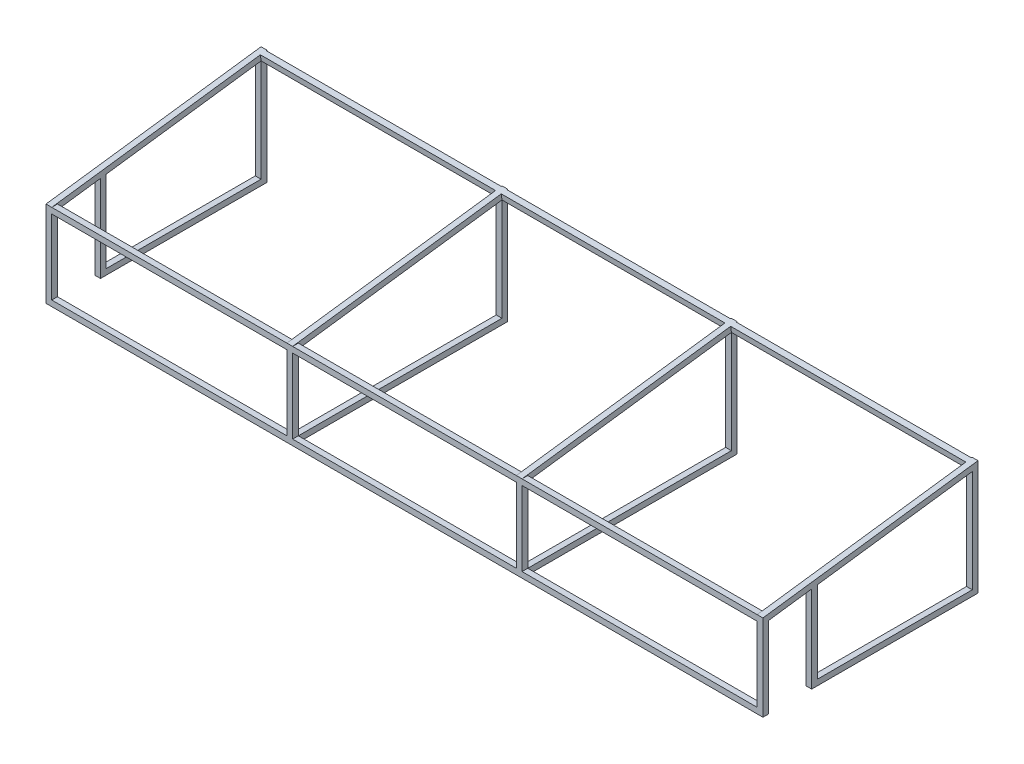
SolidWorks part; units mm, degrees
ref_plane "Front Plane" through (0, 0, 0) normal (0, 0, 1) x (1, 0, 0)
ref_plane "Top Plane" through (0, 0, 0) normal (0, 1, 0) x (1, 0, 0)
ref_plane "Right Plane" through (0, 0, 0) normal (1, 0, 0) x (0, 0, -1)
sketch "Sketch2" plane through (0, 0, 0) normal (1, 0, 0) x (0, 0, -1)
  line L0 (-2.6433, -0.3524) -> (-750, -100)
  line L1 (-750, -100) -> (-750, -400)
  line L2 (-750, -400) -> (-730, -400)
  line L3 (-730, -400) -> (-730, -117.5103)
  line L4 (-730, -117.5103) -> (0, -20.177)
  line L5 (0, -20.177) -> (0, 0) construction
  line L6 (0, -20.177) -> (-2.6433, -0.3524) construction
  line L7 (0, -20.177) -> (0, 0)
  line L8 (0, 0) -> (-2.6433, -0.3524)
  dimension "D1" = 20
  dimension "D2" = 20
  dimension "D3" = 750
  dimension "D4" = 300
  dimension "D5" = 100
extrude "Boss-Extrude2" add sketch "Sketch2" against normal blind 20 from offset 1250
sketch "Sketch3" plane through (0, 0, 0) normal (1, 0, 0) x (0, 0, -1)
  line L0 (-730, -117.5103) -> (0, -20.177) construction
  line L2 (0, -20.177) -> (-2.6433, -0.3524)
  line L3 (0, 0) -> (-750, -100) construction
  line L4 (-2.6433, -0.3524) -> (-22.4678, -2.9957)
  line L5 (-22.4678, -2.9957) -> (-19.8246, -22.8203)
  line L6 (-19.8246, -22.8203) -> (0, -20.177)
  line L7 (-730, -400) -> (-730, -117.5103) construction
  line L8 (-750, -400) -> (-730, -400)
  line L9 (-750, -400) -> (-750, -380)
  line L10 (-750, -380) -> (-730, -380)
  line L11 (-730, -400) -> (-730, -380)
  line L12 (0, -20.177) -> (0, 0) construction
  line L13 (-750, -100) -> (-730, -100)
  line L14 (-750, -100) -> (-750, -120)
  line L15 (-750, -120) -> (-730, -120)
  line L16 (-730, -100) -> (-730, -120)
  dimension "D1" = 20
extrude "Boss-Extrude3" add sketch "Sketch3" along normal mid plane 2500
pattern_linear "LPattern1" count 2 spacing 840 along (-1, 0, 0) of "Boss-Extrude2"
mirror "Mirror1" about plane through (0, 0, 0) normal (1, 0, 0) of "LPattern1", "Boss-Extrude2"
sketch "Sketch6" plane through (0, 0, 730) normal (0, 0, -1) x (-1, 0, 0)
  line L0 (1250, -400) -> (-1250, -400) construction
  line L1 (-410, -380) -> (-390, -380)
  line L2 (-410, -380) -> (-410, -400)
  line L3 (-410, -400) -> (-390, -400)
  line L4 (-390, -380) -> (-390, -400)
  line L6 (390, -380) -> (410, -380)
  line L7 (390, -380) -> (390, -400)
  line L8 (390, -400) -> (410, -400)
  line L9 (410, -380) -> (410, -400)
  line L10 (-1230, -380) -> (-1250, -380)
  line L11 (-1230, -380) -> (-1230, -400)
  line L12 (-1230, -400) -> (-1250, -400)
  line L13 (-1250, -380) -> (-1250, -400)
  line L14 (1230, -380) -> (1250, -380)
  line L15 (1230, -380) -> (1230, -400)
  line L16 (1230, -400) -> (1250, -400)
  line L17 (1250, -380) -> (1250, -400)
extrude "Boss-Extrude7" add sketch "Sketch6" along normal through all
sketch "Sketch7" plane through (0, 0, 0) normal (0, 0, -1) x (-1, 0, 0)
  line L1 (-1250, -400) -> (-1230, -400)
  line L2 (-1250, -400) -> (-1250, -20.177)
  line L3 (-1250, -20.177) -> (-1230, -20.177)
  line L4 (-1230, -400) -> (-1230, -20.177)
  line L5 (-410, -400) -> (-390, -400)
  line L6 (-410, -400) -> (-410, -20.177)
  line L7 (-410, -20.177) -> (-390, -20.177)
  line L8 (-390, -400) -> (-390, -20.177)
  line L9 (390, -400) -> (410, -400)
  line L10 (390, -400) -> (390, -20.177)
  line L11 (390, -20.177) -> (410, -20.177)
  line L12 (410, -400) -> (410, -20.177)
  line L13 (1230, -400) -> (1250, -400)
  line L14 (1230, -400) -> (1230, -20.177)
  line L15 (1230, -20.177) -> (1250, -20.177)
  line L16 (1250, -400) -> (1250, -20.177)
extrude "Boss-Extrude8" add sketch "Sketch7" against normal blind 20
sketch "Sketch8" plane through (1250, 0, 0) normal (1, 0, 0) x (0, 0, -1)
  line L0 (-730, -400) -> (-730, -117.5103)
  line L1 (-730, -117.5103) -> (-20, -22.8437)
  line L2 (-20, -22.8437) -> (0, -20.177)
  line L3 (0, -20.177) -> (0, -400)
  line L4 (0, -400) -> (-730, -400)
extrude "Cut-Extrude1" cut sketch "Sketch8" against normal blind 20
sketch "Sketch9" plane through (-1250, 0, 0) normal (-1, 0, 0) x (0, 0, 1)
  line L0 (750, -400) -> (0, -400) construction
  line L1 (560, -400) -> (580, -400)
  line L2 (560, -400) -> (560, -94.8437)
  line L3 (560, -94.8437) -> (580, -94.8437)
  line L4 (580, -400) -> (580, -94.8437)
  line L5 (730, -117.5103) -> (20, -22.8437) construction
  line L6 (730, -380) -> (730, -117.5103) construction
  dimension "D1" = 20
  dimension "D2" = 150
extrude "Boss-Extrude9" add sketch "Sketch9" against normal blind 20
sketch "Sketch10" plane through (-1250, 0, 0) normal (-1, 0, 0) x (0, 0, 1)
  line L0 (730, -380) -> (730, -117.5103) construction
  line L1 (580, -380) -> (730, -380)
  line L2 (580, -380) -> (580, -400)
  line L3 (580, -400) -> (730, -400)
  line L4 (730, -380) -> (730, -400)
  line L5 (750, -400) -> (0, -400) construction
extrude "Cut-Extrude2" cut sketch "Sketch10" against normal blind 20
sketch "Sketch11" plane through (1250, 0, 0) normal (1, 0, 0) x (0, 0, -1)
  line L0 (-20, -380) -> (-730, -380) construction
  line L1 (-560, -94.8437) -> (-580, -94.8437)
  line L2 (-560, -94.8437) -> (-560, -380)
  line L4 (-580, -94.8437) -> (-580, -380)
  line L5 (-580, -400) -> (-580, -97.5103) construction
  line L7 (0, -20.177) -> (-20, -20.177)
  line L8 (0, -20.177) -> (0, -400)
  line L10 (-20, -20.177) -> (-20, -380)
  line L11 (0, -400) -> (-580, -400)
  line L13 (-20, -380) -> (-560, -380)
  line L14 (-580, -400) -> (-580, -380)
extrude "Boss-Extrude11" add sketch "Sketch11" against normal blind 20
